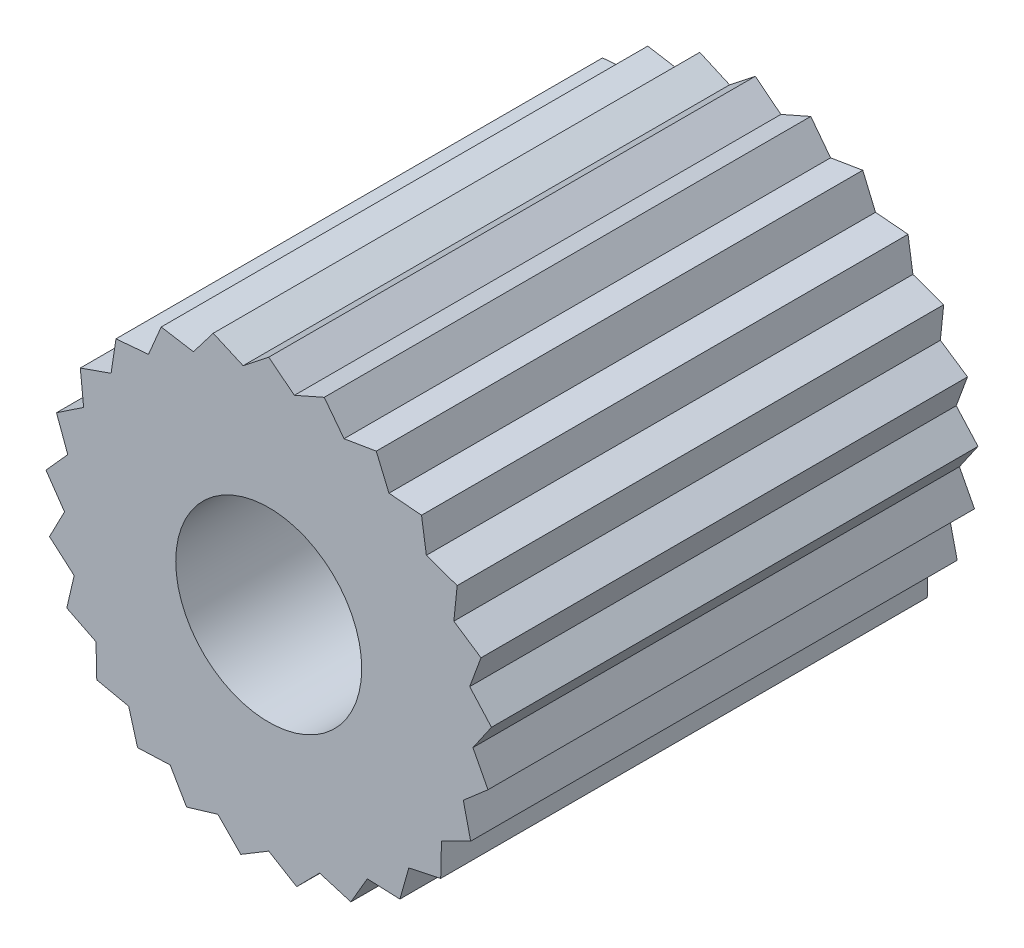
SolidWorks part; units mm, degrees
ref_plane "Front Plane" through (0, 0, 0) normal (0, 0, 1) x (1, 0, 0)
ref_plane "Top Plane" through (0, 0, 0) normal (0, 1, 0) x (1, 0, 0)
ref_plane "Right Plane" through (0, 0, 0) normal (1, 0, 0) x (0, 0, -1)
sketch "Sketch1" plane through (0, 0, 0) normal (0, 0, 1) x (1, 0, 0)
  line L0 (-10.25, 0) -> (-10.25, 3.6977) construction
  line L1 (-10.25, 0) -> (-9.3304, 3.5815) construction
  line L2 (-10.25, 0) -> (-8.4686, 3.2403) construction
  line L3 (-10.25, 0) -> (-7.7187, 2.6955) construction
  line L4 (-10.25, 0) -> (-7.1279, 1.9813) construction
  line L5 (-10.25, 0) -> (-6.7333, 1.1426) construction
  line L6 (-10.25, 0) -> (-6.5596, 0.2322) construction
  line L7 (-10.25, 0) -> (-6.6178, -0.6929) construction
  line L8 (-10.25, 0) -> (-6.9042, -1.5744) construction
  line L9 (-10.25, 0) -> (-7.4009, -2.357) construction
  line L10 (-10.25, 0) -> (-8.0765, -2.9915) construction
  line L11 (-10.25, 0) -> (-8.8888, -3.438) construction
  line L12 (-10.25, 0) -> (-9.7865, -3.6685) construction
  line L13 (-10.25, 0) -> (-10.7134, -3.6685) construction
  line L14 (-10.25, 0) -> (-11.6112, -3.438) construction
  line L15 (-10.25, 0) -> (-12.4234, -2.9915) construction
  line L16 (-10.25, 0) -> (-13.0991, -2.357) construction
  line L17 (-10.25, 0) -> (-13.5957, -1.5744) construction
  line L18 (-10.25, 0) -> (-13.8821, -0.6929) construction
  line L19 (-10.25, 0) -> (-13.9403, 0.2322) construction
  line L20 (-10.25, 0) -> (-13.7666, 1.1426) construction
  line L21 (-10.25, 0) -> (-13.372, 1.9813) construction
  line L22 (-10.25, 0) -> (-12.7812, 2.6955) construction
  line L23 (-10.25, 0) -> (-12.0313, 3.2403) construction
  line L24 (-10.25, 0) -> (-11.1695, 3.5815) construction
  line L25 (-10.25, 0) -> (-9.6998, 4.3551) construction
  line L26 (-10.25, 0) -> (-8.634, 4.0814) construction
  line L27 (-10.25, 0) -> (-7.6698, 3.5513) construction
  line L28 (-10.25, 0) -> (-6.8677, 2.7981) construction
  line L29 (-10.25, 0) -> (-6.2781, 1.869) construction
  line L30 (-10.25, 0) -> (-5.938, 0.8225) construction
  line L31 (-10.25, 0) -> (-5.8689, -0.2756) construction
  line L32 (-10.25, 0) -> (-6.0751, -1.3565) construction
  line L33 (-10.25, 0) -> (-6.5436, -2.3521) construction
  line L34 (-10.25, 0) -> (-7.245, -3.1999) construction
  line L35 (-10.25, 0) -> (-8.1352, -3.8467) construction
  line L36 (-10.25, 0) -> (-9.1583, -4.2518) construction
  line L37 (-10.25, 0) -> (-10.25, -4.3897) construction
  line L38 (-10.25, 0) -> (-11.3416, -4.2518) construction
  line L39 (-10.25, 0) -> (-12.3647, -3.8467) construction
  line L40 (-10.25, 0) -> (-13.2549, -3.1999) construction
  line L41 (-10.25, 0) -> (-13.9563, -2.3521) construction
  line L42 (-10.25, 0) -> (-14.4248, -1.3565) construction
  line L43 (-10.25, 0) -> (-14.631, -0.2756) construction
  line L44 (-10.25, 0) -> (-14.5619, 0.8225) construction
  line L45 (-10.25, 0) -> (-14.2219, 1.869) construction
  line L46 (-10.25, 0) -> (-13.6323, 2.7981) construction
  line L47 (-10.25, 0) -> (-12.8301, 3.5513) construction
  line L48 (-10.25, 0) -> (-11.8659, 4.0814) construction
  line L49 (-10.25, 0) -> (-10.8001, 4.3551) construction
  line L50 (-10.5946, 2.7283) -> (-10.25, 3)
  line L51 (-10.25, 3) -> (-9.9053, 2.7283)
  line L52 (-9.5039, 2.9057) -> (-9.2376, 2.5569)
  line L53 (-9.9053, 2.7283) -> (-9.5039, 2.9057)
  line L54 (-8.8047, 2.6289) -> (-8.6336, 2.2248)
  line L55 (-9.2376, 2.5569) -> (-8.8047, 2.6289)
  line L56 (-8.1963, 2.1869) -> (-8.1311, 1.7529)
  line L57 (-8.6336, 2.2248) -> (-8.1963, 2.1869)
  line L58 (-7.717, 1.6075) -> (-7.7617, 1.1709)
  line L59 (-8.1311, 1.7529) -> (-7.717, 1.6075)
  line L60 (-7.3968, 0.927) -> (-7.5487, 0.5153)
  line L61 (-7.7617, 1.1709) -> (-7.3968, 0.927)
  line L62 (-7.2559, 0.1884) -> (-7.5054, -0.1727)
  line L63 (-7.5487, 0.5153) -> (-7.2559, 0.1884)
  line L64 (-7.3031, -0.5621) -> (-7.6346, -0.8498)
  line L65 (-7.5054, -0.1727) -> (-7.3031, -0.5621)
  line L66 (-7.5355, -1.2773) -> (-7.9281, -1.4735)
  line L67 (-7.6346, -0.8498) -> (-7.5355, -1.2773)
  line L68 (-7.9384, -1.9123) -> (-8.3675, -2.0047)
  line L69 (-7.9281, -1.4735) -> (-7.9384, -1.9123)
  line L70 (-8.4866, -2.427) -> (-8.9251, -2.4098)
  line L71 (-8.3675, -2.0047) -> (-8.4866, -2.427)
  line L72 (-9.1456, -2.7893) -> (-9.5661, -2.6636)
  line L73 (-8.9251, -2.4098) -> (-9.1456, -2.7893)
  line L74 (-9.874, -2.9763) -> (-10.25, -2.75)
  line L75 (-9.5661, -2.6636) -> (-9.874, -2.9763)
  line L76 (-10.626, -2.9763) -> (-10.9339, -2.6636)
  line L77 (-10.25, -2.75) -> (-10.626, -2.9763)
  line L78 (-11.3543, -2.7893) -> (-11.5748, -2.4098)
  line L79 (-10.9339, -2.6636) -> (-11.3543, -2.7893)
  line L80 (-12.0133, -2.427) -> (-12.1325, -2.0047)
  line L81 (-11.5748, -2.4098) -> (-12.0133, -2.427)
  line L82 (-12.5615, -1.9123) -> (-12.5719, -1.4735)
  line L83 (-12.1325, -2.0047) -> (-12.5615, -1.9123)
  line L84 (-12.9644, -1.2773) -> (-12.8654, -0.8498)
  line L85 (-12.5719, -1.4735) -> (-12.9644, -1.2773)
  line L86 (-13.1968, -0.5621) -> (-12.9945, -0.1727)
  line L87 (-12.8654, -0.8498) -> (-13.1968, -0.5621)
  line L88 (-13.244, 0.1884) -> (-12.9512, 0.5153)
  line L89 (-12.9945, -0.1727) -> (-13.244, 0.1884)
  line L90 (-13.1031, 0.927) -> (-12.7382, 1.1709)
  line L91 (-12.9512, 0.5153) -> (-13.1031, 0.927)
  line L92 (-12.7829, 1.6075) -> (-12.3689, 1.7529)
  line L93 (-12.7382, 1.1709) -> (-12.7829, 1.6075)
  line L94 (-12.3036, 2.1869) -> (-11.8664, 2.2248)
  line L95 (-12.3689, 1.7529) -> (-12.3036, 2.1869)
  line L96 (-11.6952, 2.6289) -> (-11.2623, 2.5569)
  line L97 (-11.8664, 2.2248) -> (-11.6952, 2.6289)
  line L98 (-10.996, 2.9057) -> (-10.5946, 2.7283)
  line L99 (-11.2623, 2.5569) -> (-10.996, 2.9057)
  circle A0 centre (-10.25, 0) radius 3
  circle A1 centre (-10.25, 0) radius 2.75 construction
  point P6 (-10.5946, 2.7283)
  point P7 (-9.9053, 2.7283)
  point P32 (-10.25, 0)
  point P58 (-10.25, 0)
  point P136 (-10.25, 0)
  dimension "D1" = 0.25
  dimension "D2" = 6
  dimension "D3" = 25
  dimension "D4" = 7.2
  dimension "D5" = 25
  dimension "D6" = 25
extrude "Boss-Extrude1" add sketch "Sketch1" along normal blind 6.54 contours L51 L53 L52 L55 L54 L57 L56 L59 L58 L61 L60 L63 L62 L65 L64 L67 L66 L69 L68 L71 L70 L73 L72 L75 L74 L77 L76 L79 L78 L81 L80 L83 L82 L85 L84 L87 L86 L89 L88 L91 L90 L93 L92 L95 L94 L97 L96 L99 L98 L50
sketch "Sketch2" plane through (0, 0, 6.54) normal (0, 0, 1) x (1, 0, 0)
  circle A0 centre (-10.25, 0) radius 1.25
  dimension "D1" = 2.5
extrude "Cut-Extrude1" cut sketch "Sketch2" against normal blind 5.08
